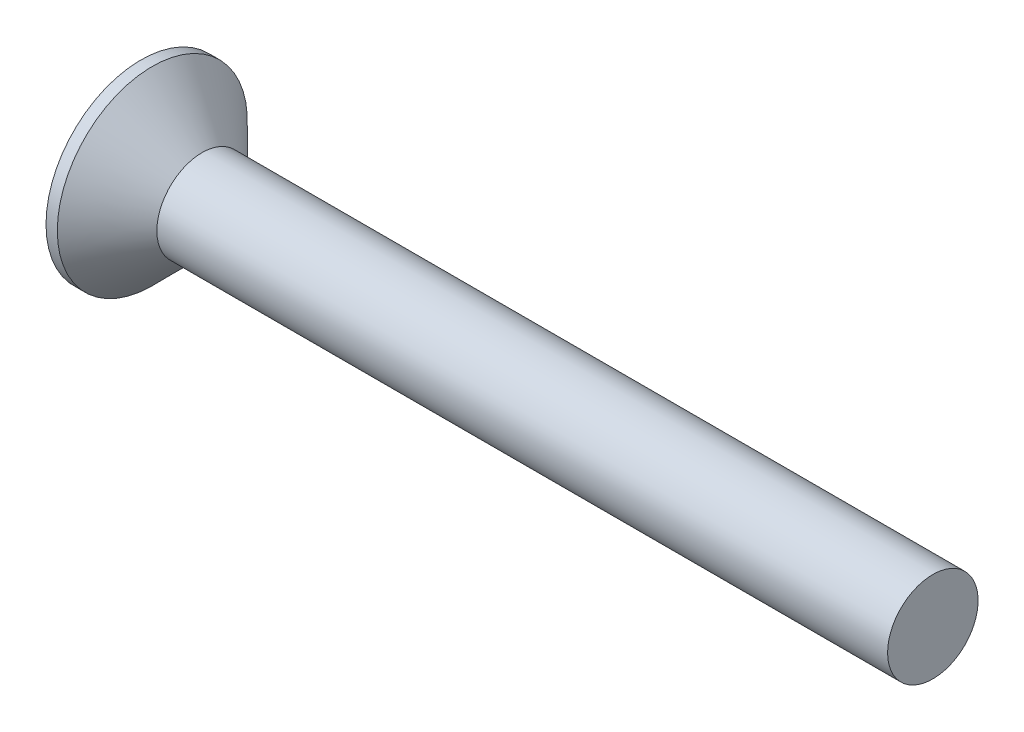
SolidWorks part; units mm, degrees
revolve "Base-Revolve" add sketch "BodySke" angle 360 about L5
sketch "BodySke" plane through (0, 0, 0) normal (0, 0, 1) x (1, 0, 0)
  line L0 (0, 0) -> (0, 4.2)
  line L1 (0, 4.2) -> (0.5, 4.2)
  line L2 (2.7, 2) -> (35, 2)
  line L3 (35, 2) -> (35, 0)
  line L4 (35, 0) -> (0, 0)
  line L5 (-6.35, 0) -> (82.55, 0) construction
  line L6 (2.7, -2) -> (35, -2) construction
  line L7 (0.5, -4.2) -> (2.7, -2) construction
  line L8 (0.5, 4.2) -> (2.7, 2)
  line L9 (0, -4.2) -> (0.5, -4.2) construction
  line L10 (3.4, 3.5875) -> (3.4, -5.9375) construction
  line L11 (0, 6.35) -> (0, -3.175) construction
  dimension "Diameter" = 4
  dimension "Length" = 35
  dimension "Head_ht" = 2.7
  dimension "Head_dia" = 8.4
  dimension "Head_ang" = 90
  dimension "D6" = 0.5
  dimension "Advance" = 0.7
  dimension "Thread_nom" = 35
cosmetic thread "ThreadCosmetic" [suppressed] parameters "Thread_length"=31.6, "Thread_minor"=3.22
extrude "Slot" [suppressed] cut sketch "Sketch2" against normal blind 1.3
sketch "Sketch2" plane through (0, 0, 0) normal (-1, 0, 0) x (0, 0, 1)
  line L0 (-4.2, -0.75) -> (4.2, -0.75)
  line L1 (-4.2, -0.75) -> (-4.2, 0.75)
  line L2 (4.2, 0.75) -> (-4.2, 0.75)
  line L3 (4.2, 0.75) -> (4.2, -0.75)
  dimension "Slot_width" = 1.5
  dimension "D1" = 0.75
  dimension "D2" = 8.4
  dimension "D3" = 4.2
ref_plane "Plane1" through (0, 0, 0) normal (0, 0, 1) x (1, 0, 0)
ref_plane "Plane2" through (0, 0, 0) normal (0, 1, 0) x (1, 0, 0)
ref_plane "Plane3" through (0, 0, 0) normal (1, 0, 0) x (0, 0, -1)
sketch "Sketch3" plane through (0, 0, 0) normal (-1, 0, 0) x (0, 0, 1)
  line L0 (-0.48, 2.23) -> (0.48, 2.23)
  line L1 (0.48, 2.23) -> (0.48, -2.23)
  line L2 (0.48, -2.23) -> (-0.48, -2.23)
  line L3 (-0.48, -2.23) -> (-0.48, 2.23)
  dimension "Cross_dia" = 4.46
  dimension "Cross_width" = 0.96
  dimension "D1" = 2.23
  dimension "D2" = 0.48
ref_plane "Plane4" through (2.65, 0, 0) normal (-1, 0, 0) x (0, 0, 1)
sketch "Sketch4" plane through (2.65, 0, 0) normal (-1, 0, 0) x (0, 0, 1)
  line L0 (-0.24, 0.24) -> (0.24, 0.24)
  line L3 (0.24, 0.24) -> (0.24, -0.24)
  line L4 (0.24, -0.24) -> (-0.24, -0.24)
  line L5 (-0.24, -0.24) -> (-0.24, 0.24)
  dimension "D2" = 0.48
  dimension "D1" = 0.48
  dimension "D3" = 0.24
  dimension "D4" = 0.24
loft "Cross" cut profiles "Sketch3", "Sketch4"
pattern_circular "CirPattern1" count 2 every 90 about axis through (0, 0, 0) along (1, 0, 0) of "Cross"
sketch "ThdSchSke" plane through (0, 0, 0) normal (0, 0, 1) x (1, 0, 0)
  line L0 (3.4, -1.61) -> (3.1269, -2)
  line L1 (3.4, -1.61) -> (3.6731, -2)
  line L2 (3.6731, -2) -> (3.6731, -2.5)
  line L3 (-3.175, 0) -> (5.1513, 0) construction
  line L5 (3.6731, -2.5) -> (3.1269, -2.5)
  line L6 (3.1269, -2.5) -> (3.1269, -2)
  line L7 (0, 4.2) -> (0, -4.2) construction
  dimension "Diameter" = 4
  dimension "Thread_minor" = 3.22
  dimension "Start" = 3.4
revolve "ThreadSchematic" [suppressed] cut sketch "ThdSchSke" angle 360 about L3
pattern_linear "ThdSchPat" [suppressed]
equation "\"D1@Sketch3\" = \"Cross_dia@Sketch3\" / 2"
equation "\"D2@Sketch3\" = \"Cross_width@Sketch3\" / 2"
equation "\"D1@Sketch4\" = \"Cross_width@Sketch3\" *.5"
equation "\"D2@Sketch4\" = \"D1@Sketch4\""
equation "\"D4@Sketch4\" = \"D2@Sketch4\" / 2"
equation "\"D3@Sketch4\" = \"D1@Sketch4\" / 2"
equation "\"D1@Sketch2\" = \"Slot_width@Sketch2\" / 2"
equation "\"D2@Sketch2\" = \"Head_dia@BodySke\""
equation "\"D3@Sketch2\" = \"D2@Sketch2\" / 2"
equation "\"Thread_length@ThreadCosmetic\" = ((sgn( (\"Length@BodySke\" - \"Advance@BodySke\" - \"Head_ht@BodySke\" ) - \"Thread_nom@BodySke\" )-1)*( (\"Length@BodySke\" - \"Advance@BodySke\" - \"Head_ht@BodySke\" ) - \"Thread_nom@BodySke\" ))/-2+ \"Thread_nom@BodySke\""
equation "\"Thread_minor@ThdSchSke\" = \"Thread_minor@ThreadCosmetic\""
equation "\"Diameter@ThdSchSke\" = \"Diameter@BodySke\""
equation "\"Overcut@ThdSchSke\" = \"Diameter@BodySke\" * 1.25"
equation "\"Start@ThdSchSke\" = 0.000001 + \"Length@BodySke\" - \"Thread_length@ThreadCosmetic\"  '---Countersunk---"
equation "\"Num_threads@ThdSchPat\" = int( \"Thread_length@ThreadCosmetic\" / \"Advance@BodySke\" + 0.999 )  + 1"
equation "\"Advance@ThdSchPat\" = \"Thread_length@ThreadCosmetic\" /  (\"Num_threads@ThdSchPat\" - 1) 'relax it"
